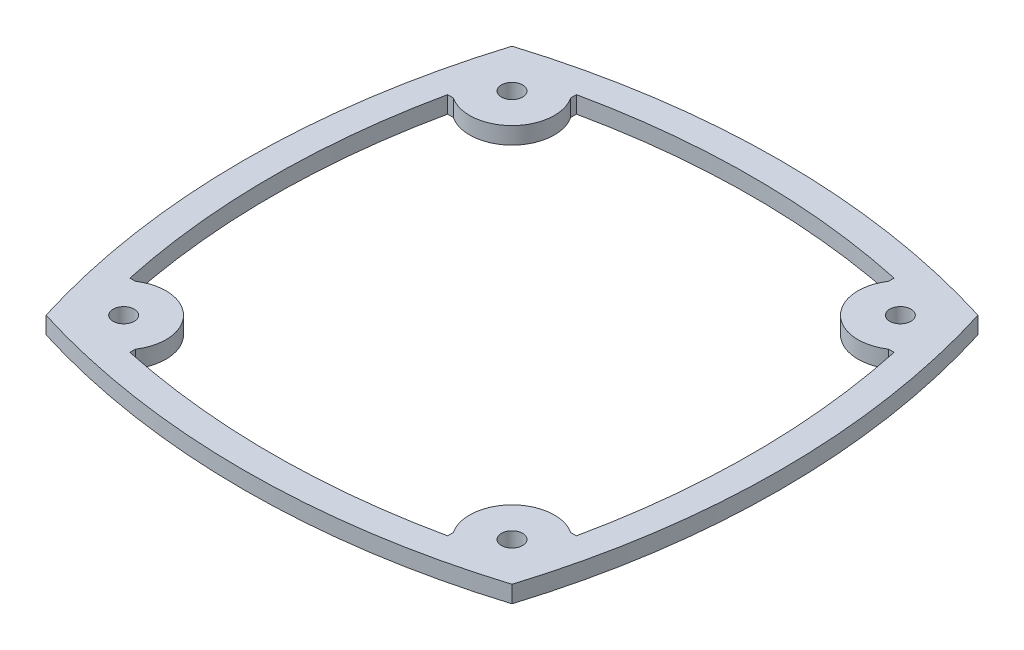
SolidWorks part; units mm, degrees
ref_plane "정면" through (0, 0, 0) normal (0, 0, 1) x (1, 0, 0)
ref_plane "윗면" through (0, 0, 0) normal (0, 1, 0) x (1, 0, 0)
ref_plane "우측면" through (0, 0, 0) normal (1, 0, 0) x (0, 0, -1)
sketch "스케치1" plane through (0, 0, 0) normal (0, 1, 0) x (1, 0, 0)
  line L0 (-38, 0) -> (38, 0) construction
  line L1 (0, 38) -> (0, -38) construction
  line L4 (-22.5, 30.8166) -> (-22.5, 31.6167)
  line L6 (-30.8166, 22.5) -> (-31.6167, 22.5)
  line L7 (30.8166, 22.5) -> (31.6167, 22.5)
  line L9 (22.5, 30.8166) -> (22.5, 31.6167)
  line L11 (22.5, -30.8166) -> (22.5, -31.6167)
  line L13 (30.8166, -22.5) -> (31.6167, -22.5)
  line L14 (-30.8166, -22.5) -> (-31.6167, -22.5)
  line L16 (-22.5, -30.8166) -> (-22.5, -31.6167)
  arc A0 (33, -33) -> (-33, -33) centre (0, 73.4) cw
  arc A1 (-33, 33) -> (33, 33) centre (0, -73.4) cw
  arc A2 (33, 33) -> (33, -33) centre (-73.4, 0) cw
  arc A3 (-33, -33) -> (-33, 33) centre (73.4, 0) cw
  arc A5 (-22.5, 31.6167) -> (0, 34) centre (0, -73.4) cw
  arc A8 (-30.8166, 22.5) -> (-22.5, 30.8166) centre (-27.5, 27.5) ccw
  arc A10 (-34, 0) -> (-31.6167, 22.5) centre (73.4, 0) cw
  arc A13 (31.6167, 22.5) -> (34, 0) centre (-73.4, 0) cw
  arc A15 (22.5, 30.8166) -> (30.8166, 22.5) centre (27.5, 27.5) ccw
  arc A18 (0, 34) -> (22.5, 31.6167) centre (0, -73.4) cw
  arc A19 (22.5, -31.6167) -> (0, -34) centre (0, 73.4) cw
  arc A20 (-22.5, -30.8166) -> (-30.8166, -22.5) centre (-27.5, -27.5) ccw
  arc A21 (30.8166, -22.5) -> (22.5, -30.8166) centre (27.5, -27.5) ccw
  arc A22 (0, -34) -> (-22.5, -31.6167) centre (0, 73.4) cw
  arc A23 (-31.6167, -22.5) -> (-34, 0) centre (73.4, 0) cw
  arc A24 (34, 0) -> (31.6167, -22.5) centre (-73.4, 0) cw
  point P4 (0, 38)
  point P6 (-38, 0)
  point P7 (38, 0)
  point P8 (0, -38)
  point P17 (-31.9721, -23.5)
  dimension "D8" = 4
  dimension "D9" = 4
  dimension "D10" = 6
  dimension "D11" = 4
  dimension "D1" = 66
  dimension "D2" = 76
  dimension "D3" = 66
  dimension "D4" = 27.5
  dimension "D5" = 27.5
  dimension "D6" = 5
  dimension "D7" = 5
extrude "보스-돌출1" add sketch "스케치1" along normal blind 2.4
sketch "스케치2" plane through (0, 0, 0) normal (0, 1, 0) x (1, 0, 0)
  line L0 (-23.5, 30.5) -> (-23.5, 32.4216)
  line L1 (30.5, 23.5) -> (32.4216, 23.5)
  line L2 (-24.5, 30.1458) -> (-24.5, 33.2209)
  line L3 (-30.5, 23.5) -> (-32.4216, 23.5)
  line L4 (-30.1458, 24.5) -> (-33.2209, 24.5)
  line L5 (30.1458, 24.5) -> (33.2209, 24.5)
  line L6 (23.5, 30.5) -> (23.5, 32.4216)
  line L7 (24.5, 30.1458) -> (24.5, 33.2209)
  line L8 (23.5, -30.5) -> (23.5, -32.4216)
  line L9 (24.5, -30.1458) -> (24.5, -33.2209)
  line L10 (30.5, -23.5) -> (32.4216, -23.5)
  line L11 (30.1458, -24.5) -> (33.2209, -24.5)
  line L12 (-30.5, -23.5) -> (-32.4216, -23.5)
  line L13 (-30.1458, -24.5) -> (-33.2209, -24.5)
  line L14 (-23.5, -30.5) -> (-23.5, -32.4216)
  line L15 (-24.5, -30.1458) -> (-24.5, -33.2209)
  arc A0 (-30.5, 23.5) -> (-23.5, 30.5) centre (-27.5, 27.5) ccw
  arc A1 (-30.1458, 24.5) -> (-24.5, 30.1458) centre (-27.5, 27.5) ccw
  arc A2 (-34.9995, 0) -> (-32.4216, 23.5) centre (73.4, 0) cw
  arc A4 (-23.5, 32.4216) -> (0, 34.9995) centre (0, -73.4) cw
  arc A6 (-35.9995, 0) -> (-33.2209, 24.5) centre (73.4, 0) cw
  arc A7 (-24.5, 33.2209) -> (0, 35.9995) centre (0, -73.4) cw
  arc A8 (23.5, 30.5) -> (30.5, 23.5) centre (27.5, 27.5) ccw
  arc A9 (24.5, 30.1458) -> (30.1458, 24.5) centre (27.5, 27.5) ccw
  arc A10 (0, 34.9995) -> (23.5, 32.4216) centre (0, -73.4) cw
  arc A11 (32.4216, 23.5) -> (34.9995, 0) centre (-73.4, 0) cw
  arc A12 (0, 35.9995) -> (24.5, 33.2209) centre (0, -73.4) cw
  arc A13 (33.2209, 24.5) -> (35.9995, 0) centre (-73.4, 0) cw
  arc A14 (30.5, -23.5) -> (23.5, -30.5) centre (27.5, -27.5) ccw
  arc A15 (30.1458, -24.5) -> (24.5, -30.1458) centre (27.5, -27.5) ccw
  arc A16 (34.9995, 0) -> (32.4216, -23.5) centre (-73.4, 0) cw
  arc A17 (23.5, -32.4216) -> (0, -34.9995) centre (0, 73.4) cw
  arc A18 (35.9995, 0) -> (33.2209, -24.5) centre (-73.4, 0) cw
  arc A19 (24.5, -33.2209) -> (0, -35.9995) centre (0, 73.4) cw
  arc A20 (-23.5, -30.5) -> (-30.5, -23.5) centre (-27.5, -27.5) ccw
  arc A21 (-24.5, -30.1458) -> (-30.1458, -24.5) centre (-27.5, -27.5) ccw
  arc A22 (0, -34.9995) -> (-23.5, -32.4216) centre (0, 73.4) cw
  arc A23 (-32.4216, -23.5) -> (-34.9995, 0) centre (73.4, 0) cw
  arc A24 (0, -35.9995) -> (-24.5, -33.2209) centre (0, 73.4) cw
  arc A25 (-33.2209, -24.5) -> (-35.9995, 0) centre (73.4, 0) cw
  point P1 (-86.3186, 10.2121)
  point P3 (0, 0)
  point P8 (0, 0)
  point P38 (0, 0)
  dimension "D1" = 1
  dimension "D4" = 1
  dimension "D3" = 1
  dimension "D5" = 1
  dimension "D6" = 4
extrude "컷-돌출2" cut sketch "스케치2" along normal blind 1
sketch "스케치3" plane through (0, 0, 0) normal (0, 1, 0) x (1, 0, 0)
  circle A0 centre (-27.5, 27.5) radius 1.5
  circle A1 centre (27.5, 27.5) radius 1.5
  circle A2 centre (27.5, -27.5) radius 1.5
  circle A3 centre (-27.5, -27.5) radius 1.5
  dimension "D1" = 3
extrude "컷-돌출3" cut sketch "스케치3" along normal through all
